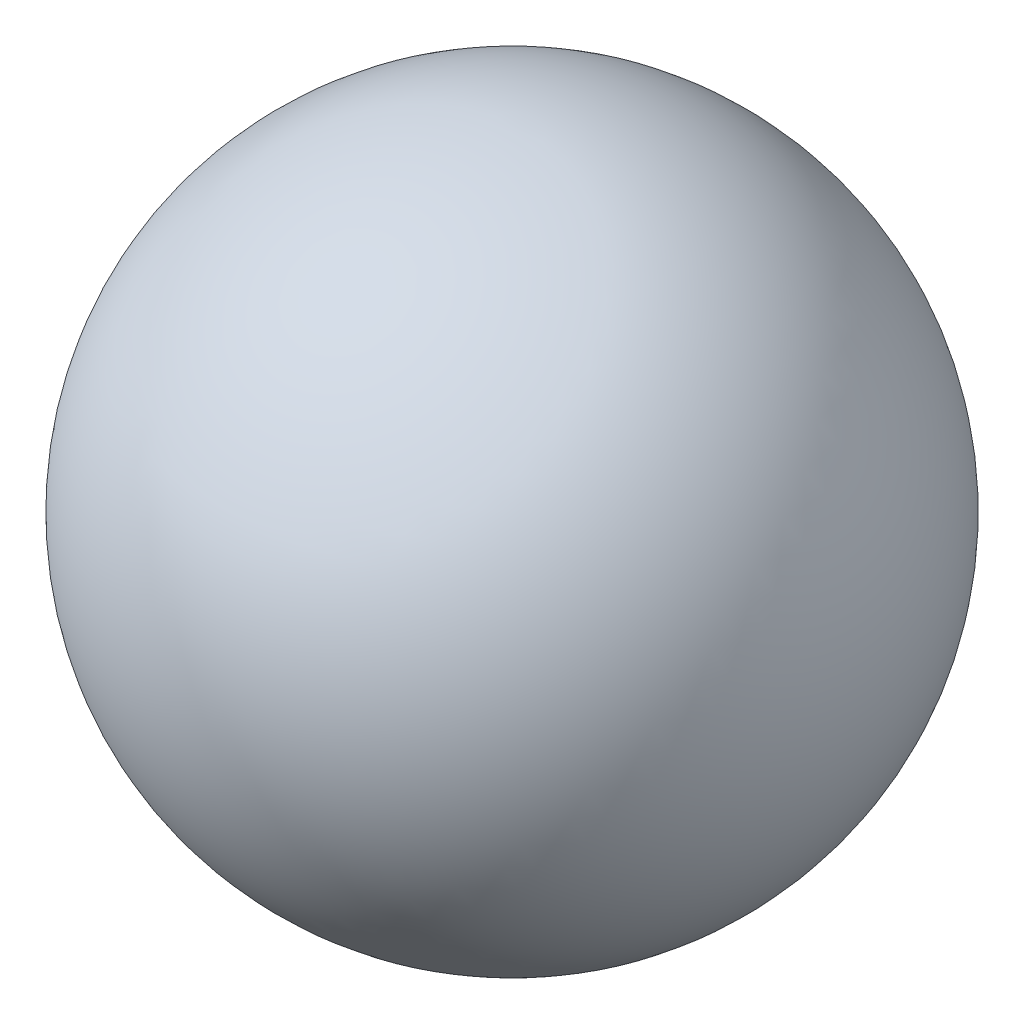
SolidWorks part; units mm, degrees
ref_plane "Front" through (0, 0, 0) normal (0, 0, 1) x (1, 0, 0)
ref_plane "Top" through (0, 0, 0) normal (0, 1, 0) x (1, 0, 0)
ref_plane "Right" through (0, 0, 0) normal (1, 0, 0) x (0, 0, -1)
sketch "Sketch2" plane through (0, 0, 0) normal (1, 0, 0) x (0, 0, -1)
  line L0 (0, -2.25) -> (0, 2.25)
  circle A0 centre (0, 0) radius 2.25 construction
  arc A1 (0, 2.25) -> (0, -2.25) centre (0, 0) cw
  dimension "D1" = 4.5
revolve "Revolve1" add sketch "Sketch2" angle 360 about L0
sketch "Right Plane Cut Guide" plane through (0, 0, 0) normal (1, 0, 0) x (0, 0, -1)
  circle A2 centre (0, 0) radius 2.3
  circle A3 centre (0, 0) radius 2.3
  dimension "D1" = 0.05
